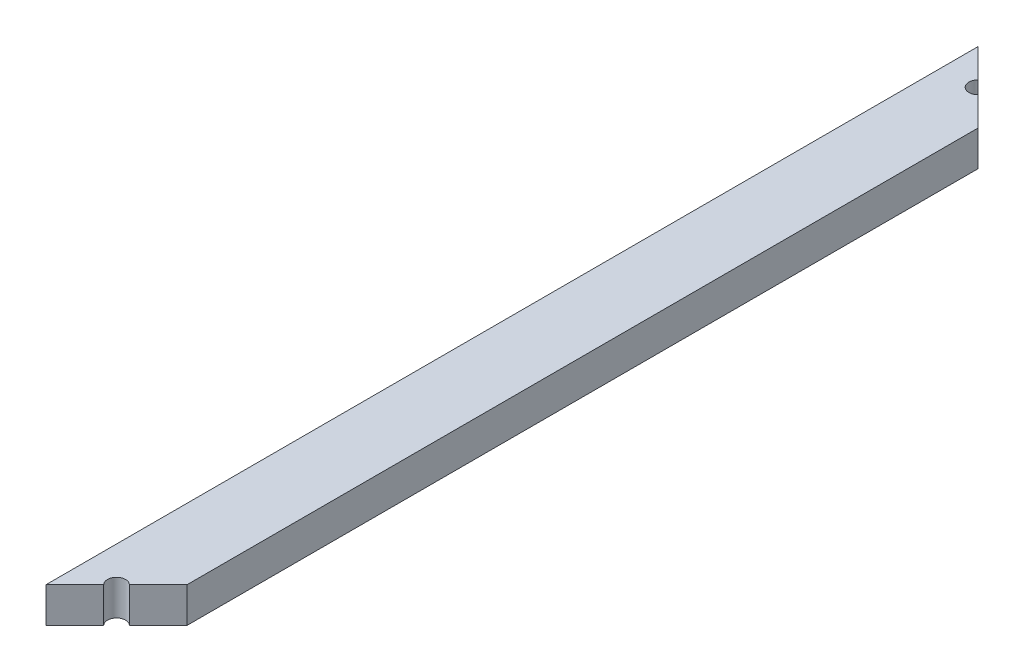
SolidWorks part; units mm, degrees
ref_plane "Front Plane" through (0, 0, 0) normal (0, 0, 1) x (1, 0, 0)
ref_plane "Top Plane" through (0, 0, 0) normal (0, 1, 0) x (1, 0, 0)
ref_plane "Right Plane" through (0, 0, 0) normal (1, 0, 0) x (0, 0, -1)
sketch "Sketch1" plane through (0, 0, 0) normal (0, 0, 1) x (1, 0, 0)
  line L1 (0, 0) -> (14, 0)
  line L2 (0, 0) -> (0, 7)
  line L3 (0, 7) -> (14, 7)
  line L4 (14, 0) -> (14, 7)
  dimension "D1" = 7
  dimension "D2" = 14
extrude "Boss-Extrude1" add sketch "Sketch1" along normal blind 185
sketch "Sketch2" plane through (0, 7, 0) normal (0, 1, 0) x (1, 0, 0)
  line L0 (0, 0) -> (14, -14)
  line L1 (14, -185) -> (14, 0) construction
  line L2 (14, -14) -> (14, 0)
  line L3 (14, 0) -> (0, 0)
  line L4 (0, -92.5) -> (14, -92.5) construction
  line L5 (0, -185) -> (0, 0) construction
  line L6 (14, -185) -> (0, -185)
  line L7 (14, -171) -> (14, -185)
  line L8 (0, -185) -> (14, -171)
  dimension "D1" = 45
extrude "Cut-Extrude1" cut sketch "Sketch2" against normal through all
sketch "Sketch3" plane through (0, 7, 0) normal (0, 1, 0) x (1, 0, 0)
  line L0 (0, 0) -> (14, -14) construction
  line L1 (0, -92.5) -> (14, -92.5) construction
  line L2 (0, -185) -> (0, 0) construction
  line L3 (14, -171) -> (14, -14) construction
  line L4 (14, -171) -> (0, -185) construction
  line L5 (8.2728, -176.7272) -> (5.7272, -179.2728)
  line L6 (5.7272, -5.7272) -> (8.2728, -8.2728)
  arc A0 (5.7272, -5.7272) -> (8.2728, -8.2728) centre (7, -7) ccw
  arc A1 (5.7272, -179.2728) -> (8.2728, -176.7272) centre (7, -178) cw
  dimension "D1" = 3.6
extrude "Cut-Extrude2" cut sketch "Sketch3" against normal through all
